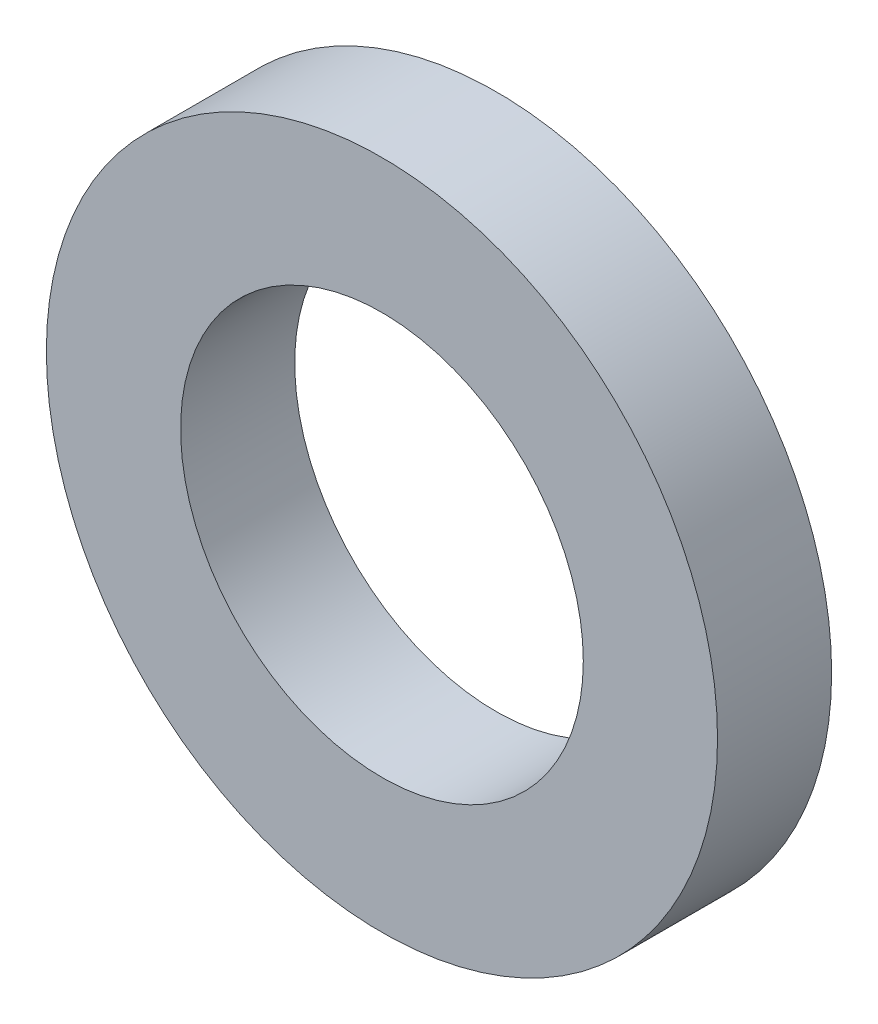
SolidWorks part; units mm, degrees
ref_plane "Front Plane" through (0, 0, 0) normal (0, 0, 1) x (1, 0, 0)
ref_plane "Top Plane" through (0, 0, 0) normal (0, 1, 0) x (1, 0, 0)
ref_plane "Right Plane" through (0, 0, 0) normal (1, 0, 0) x (0, 0, -1)
sketch "Sketch1" plane through (0, 0, 0) normal (0, 0, 1) x (1, 0, 0)
  circle A0 centre (0, 0) radius 3
  circle A1 centre (0, 0) radius 5
  dimension "D1" = 6
  dimension "D2" = 10
extrude "Boss-Extrude1" add sketch "Sketch1" along normal blind 1.7
equation "\"smallPulleyTeeth\"= 15"
equation "\"largePulleyTeeth\"= 40"
equation "\"eighthThick\"= 2.9mm"
equation "\"sixteenthThick\"= 1.7mm"
equation "\"quarterThick\"=5.9mm"
equation "\"OD\"= 145mm"
equation "\"puckAngle\"= 60.5deg"
equation "\"puckDiam\"= 76.5mm"
equation "\"axlePress\"= 5.9mm"
equation "\"press\"= 0.2mm"
equation "\"wheelClear\"= 0.3mm"
equation "\"10-32clear\"= 4.5mm"
equation "\"6-32clear\"= 3.3mm"
equation "\"8-32clear\"= 4.0mm"
equation "\"D1@Boss-Extrude1\"=\"sixteenthThick\""
